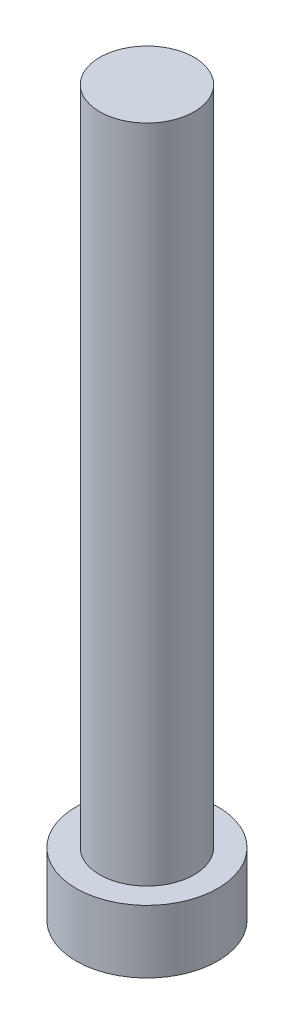
SolidWorks part; units mm, degrees
ref_plane "Front Plane" through (0, 0, 0) normal (0, 0, 1) x (1, 0, 0)
ref_plane "Top Plane" through (0, 0, 0) normal (0, 1, 0) x (1, 0, 0)
ref_plane "Right Plane" through (0, 0, 0) normal (1, 0, 0) x (0, 0, -1)
sketch "Sketch1" plane through (0, 0, 0) normal (0, 1, 0) x (1, 0, 0)
  circle A0 centre (0, 0) radius 22.5
  dimension "D1" = 45
extrude "Boss-Extrude1" add sketch "Sketch1" along normal blind 20
sketch "Sketch2" plane through (0, 20, 0) normal (0, 1, 0) x (1, 0, 0)
  circle A0 centre (0, 0) radius 15
  dimension "D1" = 30
extrude "Boss-Extrude2" add sketch "Sketch2" along normal blind 210
